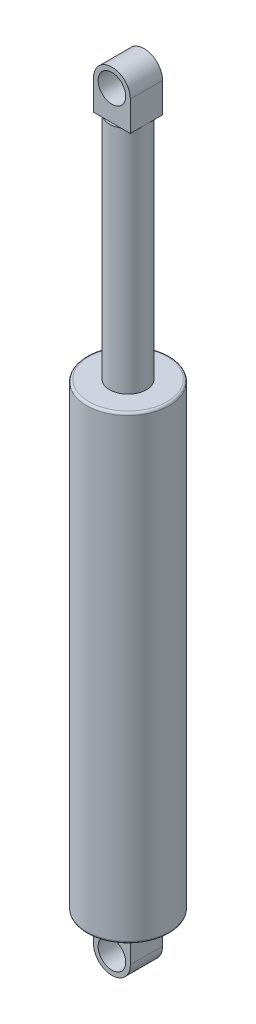
SolidWorks part; units mm, degrees
ref_plane "Front Plane" through (0, 0, 0) normal (0, 0, 1) x (1, 0, 0)
ref_plane "Top Plane" through (0, 0, 0) normal (0, 1, 0) x (1, 0, 0)
ref_plane "Right Plane" through (0, 0, 0) normal (1, 0, 0) x (0, 0, -1)
sketch "Sketch1" plane through (0, 0, 0) normal (0, 1, 0) x (1, 0, 0)
  circle A0 centre (0, 0) radius 4
  dimension "D1" = 8
extrude "Boss-Extrude1" add sketch "Sketch1" along normal blind 50
sketch "Sketch2" plane through (0, 0, 0) normal (0, -1, 0) x (-1, 0, 0)
  circle A0 centre (0, 0) radius 9
extrude "Boss-Extrude2" add sketch "Sketch2" along normal blind 100
fillet "Fillet1" radius 0.5 2 edges at (0, 0, -9) (0, -100, -9)
sketch "Sketch4" plane through (0, 0, 0) normal (0, 0, 1) x (1, 0, 0)
  line L0 (0, -107.7399) -> (0, -96.2036) construction
  line L1 (-8.5, -100) -> (8.5, -100) construction
  line L3 (-4, -106.5072) -> (-4, -100)
  line L4 (-4, -100) -> (4, -100)
  line L5 (4, -106.5072) -> (4, -100)
  line L6 (-4, -106.5072) -> (4, -100) construction
  line L7 (-4, -100) -> (4, -106.5072) construction
  line L8 (-4, -106.5072) -> (4, -106.5072) construction
  arc A0 (-4, -106.5072) -> (4, -106.5072) centre (0, -106.5072) ccw
  point P3 (0, -103.2536)
  dimension "D1" = 4
extrude "Boss-Extrude4" add sketch "Sketch4" along normal mid plane 7
sketch "Sketch5" plane through (0, 0, 0) normal (0, 0, 1) x (1, 0, 0)
  line L0 (0, 50) -> (0, 56.5) construction
  line L2 (4, 50) -> (-4, 50) construction
  line L4 (-4, 56.5) -> (-4, 50)
  line L5 (-4, 50) -> (4, 50)
  line L6 (4, 56.5) -> (4, 50)
  line L7 (-4, 56.5) -> (4, 50) construction
  line L8 (-4, 50) -> (4, 56.5) construction
  arc A1 (4, 56.5) -> (-4, 56.5) centre (0, 56.5) ccw
  point P5 (0, 53.25)
  dimension "D1" = 4
  dimension "D2" = 6.5
  dimension "D3" = 8
extrude "Boss-Extrude6" add sketch "Sketch5" along normal mid plane 7
sketch "Sketch7" plane through (0, 0, 3.5) normal (0, 0, 1) x (1, 0, 0)
  circle A0 centre (0, 56.5) radius 3
  arc A1 (4, 56.5) -> (-4, 56.5) centre (0, 56.5) ccw construction
  dimension "D1" = 6
extrude "Cut-Extrude1" cut sketch "Sketch7" against normal through all contours A0
cosmetic thread "Cosmetic Thread6" parameters "D2"=10
sketch "Sketch9" plane through (0, 0, 3.5) normal (0, 0, 1) x (1, 0, 0)
  circle A0 centre (0, -106.5072) radius 3
  arc A1 (-4, -106.5072) -> (4, -106.5072) centre (0, -106.5072) ccw construction
  dimension "D1" = 6
extrude "Cut-Extrude2" cut sketch "Sketch9" against normal through all
cosmetic thread "Cosmetic Thread5" parameters "D2"=10
